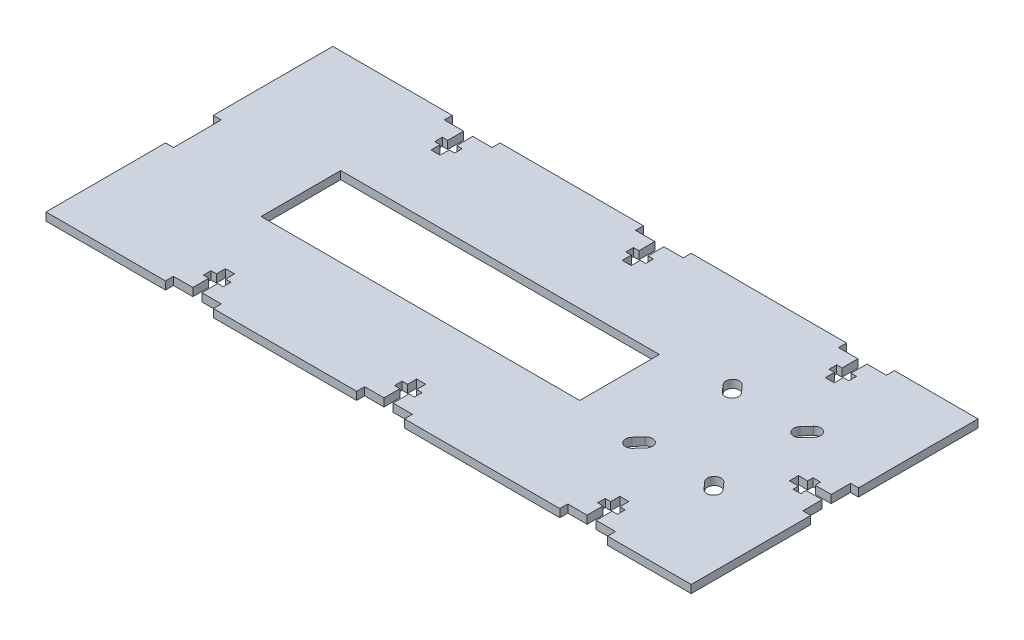
SolidWorks part; units mm, degrees
ref_plane "Front Plane" through (0, 0, 0) normal (0, 0, 1) x (1, 0, 0)
ref_plane "Top Plane" through (0, 0, 0) normal (0, 1, 0) x (1, 0, 0)
ref_plane "Right Plane" through (0, 0, 0) normal (1, 0, 0) x (0, 0, -1)
sketch "Sketch2" plane through (0, 0, 0) normal (0, 1, 0) x (1, 0, 0)
  line L0 (-102.87, -45.72) -> (-64.77, -45.72)
  line L1 (-102.87, 45.72) -> (102.87, 45.72) construction
  line L2 (-102.87, 45.72) -> (-102.87, -45.72) construction
  line L3 (-102.87, -45.72) -> (102.87, -45.72) construction
  line L4 (102.87, 45.72) -> (102.87, -45.72) construction
  line L5 (-102.87, 45.72) -> (102.87, -45.72) construction
  line L6 (-102.87, -45.72) -> (102.87, 45.72) construction
  line L7 (-64.77, -45.72) -> (-64.77, -43.18)
  line L9 (-49.53, -43.18) -> (-49.53, -45.72)
  line L10 (-49.53, -45.72) -> (-3.81, -45.72)
  line L11 (-3.81, -45.72) -> (-3.81, -43.18)
  line L12 (-3.81, -43.18) -> (11.43, -43.18) construction
  line L13 (11.43, -43.18) -> (11.43, -45.72)
  line L14 (11.43, -45.72) -> (60.96, -45.72)
  line L15 (60.96, -45.72) -> (60.96, -43.18)
  line L16 (60.96, -43.18) -> (76.2, -43.18) construction
  line L17 (76.2, -43.18) -> (76.2, -45.72)
  line L18 (76.2, -45.72) -> (102.87, -45.72)
  line L21 (-102.87, 0) -> (102.87, 0) construction
  line L22 (76.2, 43.18) -> (76.2, 45.72)
  line L23 (60.96, 43.18) -> (76.2, 43.18) construction
  line L24 (60.96, 45.72) -> (60.96, 43.18)
  line L25 (11.43, 43.18) -> (11.43, 45.72)
  line L26 (-3.81, 43.18) -> (11.43, 43.18) construction
  line L27 (-3.81, 45.72) -> (-3.81, 43.18)
  line L28 (-49.53, 43.18) -> (-49.53, 45.72)
  line L29 (-64.77, 43.18) -> (-49.53, 43.18) construction
  line L30 (-64.77, 45.72) -> (-64.77, 43.18)
  line L31 (-102.87, 45.72) -> (-64.77, 45.72)
  line L32 (-49.53, 45.72) -> (-3.81, 45.72)
  line L33 (11.43, 45.72) -> (60.96, 45.72)
  line L34 (76.2, 45.72) -> (102.87, 45.72)
  line L35 (-102.87, 45.72) -> (-102.87, 7.62)
  line L36 (-102.87, 7.62) -> (-100.33, 7.62)
  line L37 (-100.33, 7.62) -> (-100.33, -7.62)
  line L38 (-100.33, -7.62) -> (-102.87, -7.62)
  line L39 (-102.87, -7.62) -> (-102.87, -45.72)
  line L40 (0, 45.72) -> (0, -45.72) construction
  line L41 (100.33, -7.62) -> (102.87, -7.62)
  line L42 (102.87, 7.62) -> (100.33, 7.62)
  line L43 (100.33, 7.62) -> (100.33, -7.62) construction
  line L44 (102.87, 45.72) -> (102.87, 7.62)
  line L45 (102.87, -7.62) -> (102.87, -45.72)
  line L46 (-58.5978, -43.18) -> (-58.5978, -38.1)
  line L47 (-58.5978, -38.1) -> (-60.325, -38.1)
  line L48 (-60.325, -38.1) -> (-60.325, -35.668)
  line L49 (-60.325, -35.668) -> (-58.5978, -35.668)
  line L50 (-58.5978, -35.668) -> (-58.5978, -32.766)
  line L51 (-58.5978, -32.766) -> (-55.7022, -32.766)
  line L52 (-64.77, -43.18) -> (-58.5978, -43.18)
  line L53 (-49.53, -43.18) -> (-55.7022, -43.18)
  line L54 (-55.7022, -43.18) -> (-55.7022, -38.1)
  line L55 (-55.7022, -38.1) -> (-53.975, -38.1)
  line L56 (-53.975, -38.1) -> (-53.975, -35.668)
  line L57 (-64.77, -43.18) -> (-49.53, -43.18) construction
  line L58 (-57.15, -43.18) -> (-57.15, -32.766) construction
  line L59 (-53.975, -35.668) -> (-55.7022, -35.668)
  line L60 (-55.7022, -35.668) -> (-55.7022, -32.766)
  line L61 (-3.81, -43.18) -> (2.3622, -43.18)
  line L62 (2.3622, -43.18) -> (2.3622, -38.1)
  line L63 (2.3622, -38.1) -> (0.635, -38.1)
  line L64 (0.635, -38.1) -> (0.635, -35.6679)
  line L65 (0.635, -35.6679) -> (2.3622, -35.6679)
  line L66 (2.3622, -35.6679) -> (2.3622, -32.766)
  line L67 (2.3622, -32.766) -> (5.2578, -32.766)
  line L68 (3.81, -43.18) -> (3.81, -32.766) construction
  line L69 (11.43, -43.18) -> (5.2578, -43.18)
  line L70 (5.2578, -43.18) -> (5.2578, -38.1)
  line L71 (5.2578, -38.1) -> (6.985, -38.1)
  line L72 (6.985, -38.1) -> (6.985, -35.6679)
  line L73 (6.985, -35.6679) -> (5.2578, -35.6679)
  line L74 (5.2578, -35.6679) -> (5.2578, -32.766)
  line L75 (68.58, -43.18) -> (68.58, -32.766) construction
  line L76 (60.96, -43.18) -> (67.1322, -43.18)
  line L77 (67.1322, -43.18) -> (67.1322, -38.1)
  line L78 (67.1322, -38.1) -> (65.405, -38.1)
  line L79 (65.405, -38.1) -> (65.405, -35.6679)
  line L80 (65.405, -35.6679) -> (67.1322, -35.6679)
  line L81 (67.1322, -35.6679) -> (67.1322, -32.766)
  line L82 (67.1322, -32.766) -> (70.0278, -32.766)
  line L83 (70.0278, -35.6679) -> (70.0278, -32.766)
  line L84 (71.755, -35.6679) -> (70.0278, -35.6679)
  line L85 (71.755, -38.1) -> (71.755, -35.6679)
  line L86 (70.0278, -38.1) -> (71.755, -38.1)
  line L87 (76.2, -43.18) -> (70.0278, -43.18)
  line L88 (70.0278, -43.18) -> (70.0278, -38.1)
  line L89 (76.2, 43.18) -> (70.0278, 43.18)
  line L90 (70.0278, 43.18) -> (70.0278, 38.1)
  line L91 (70.0278, 38.1) -> (71.755, 38.1)
  line L92 (71.755, 38.1) -> (71.755, 35.6679)
  line L93 (71.755, 35.6679) -> (70.0278, 35.6679)
  line L94 (70.0278, 35.6679) -> (70.0278, 32.766)
  line L95 (67.1322, 32.766) -> (70.0278, 32.766)
  line L96 (67.1322, 35.6679) -> (67.1322, 32.766)
  line L97 (65.405, 35.6679) -> (67.1322, 35.6679)
  line L98 (65.405, 38.1) -> (65.405, 35.6679)
  line L99 (67.1322, 38.1) -> (65.405, 38.1)
  line L100 (67.1322, 43.18) -> (67.1322, 38.1)
  line L101 (60.96, 43.18) -> (67.1322, 43.18)
  line L102 (11.43, 43.18) -> (5.2578, 43.18)
  line L103 (5.2578, 43.18) -> (5.2578, 38.1)
  line L104 (5.2578, 38.1) -> (6.985, 38.1)
  line L105 (6.985, 38.1) -> (6.985, 35.6679)
  line L106 (6.985, 35.6679) -> (5.2578, 35.6679)
  line L107 (5.2578, 35.6679) -> (5.2578, 32.766)
  line L108 (2.3622, 32.766) -> (5.2578, 32.766)
  line L109 (0.635, 35.6679) -> (2.3622, 35.6679)
  line L110 (2.3622, 38.1) -> (0.635, 38.1)
  line L111 (0.635, 38.1) -> (0.635, 35.6679)
  line L112 (2.3622, 43.18) -> (2.3622, 38.1)
  line L113 (-3.81, 43.18) -> (2.3622, 43.18)
  line L114 (-49.53, 43.18) -> (-55.7022, 43.18)
  line L115 (-55.7022, 43.18) -> (-55.7022, 38.1)
  line L116 (-55.7022, 38.1) -> (-53.975, 38.1)
  line L117 (-53.975, 38.1) -> (-53.975, 35.6679)
  line L118 (-53.975, 35.6679) -> (-55.7022, 35.6679)
  line L119 (-55.7022, 35.6679) -> (-55.7022, 32.766)
  line L120 (-58.5978, 32.766) -> (-55.7022, 32.766)
  line L121 (-58.5978, 35.6679) -> (-58.5978, 32.766)
  line L122 (-60.325, 35.6679) -> (-58.5978, 35.6679)
  line L123 (-60.325, 38.1) -> (-60.325, 35.6679)
  line L124 (-58.5978, 38.1) -> (-60.325, 38.1)
  line L125 (-58.5978, 43.18) -> (-58.5978, 38.1)
  line L126 (-64.77, 43.18) -> (-58.5978, 43.18)
  line L127 (2.3622, 35.6679) -> (2.3622, 32.766)
  line L128 (100.33, -1.4478) -> (95.25, -1.4478)
  line L129 (95.25, -1.4478) -> (95.25, -3.175)
  line L130 (95.25, -3.175) -> (92.8179, -3.175)
  line L131 (92.8179, -3.175) -> (92.8179, -1.4478)
  line L132 (92.8179, -1.4478) -> (89.916, -1.4478)
  line L133 (89.916, -1.4478) -> (89.916, 1.4478)
  line L134 (100.33, -1.4478) -> (100.33, -7.62)
  line L135 (92.8179, 1.4478) -> (89.916, 1.4478)
  line L136 (92.8179, 3.175) -> (92.8179, 1.4478)
  line L137 (95.25, 3.175) -> (92.8179, 3.175)
  line L138 (95.25, 1.4478) -> (95.25, 3.175)
  line L139 (100.33, 1.4478) -> (95.25, 1.4478)
  line L140 (100.33, 1.4478) -> (100.33, 7.62)
  point P0 (0, 0)
  point P128 (89.916, 0)
  dimension "D1" = 205.74
  dimension "D2" = 91.44
  dimension "D3" = 38.1
  dimension "D4" = 15.24
  dimension "D5" = 2.54
  dimension "D6" = 45.72
  dimension "D7" = 49.53
  dimension "D8" = 15.24
  dimension "D9" = 2.54
  dimension "D10" = 12.954
  dimension "D11" = 5.08
  dimension "D12" = 2.432
  dimension "D13" = 6.35
  dimension "D14" = 2.8956
  dimension "D15" = 12.954
  dimension "D16" = 5.08
  dimension "D17" = 2.432
  dimension "D18" = 6.35
  dimension "D19" = 2.8956
  dimension "D20" = 12.954
  dimension "D21" = 5.08
  dimension "D22" = 2.432
  dimension "D23" = 6.35
  dimension "D24" = 2.8956
  dimension "D25" = 12.954
  dimension "D26" = 2.432
  dimension "D27" = 5.08
  dimension "D28" = 2.8956
  dimension "D29" = 6.35
extrude "Boss-Extrude1" add sketch "Sketch2" against normal blind 2.54
sketch "Sketch3" plane through (0, 0, 0) normal (0, 1, 0) x (1, 0, 0)
  line L0 (0, 0) -> (67.31, 0) construction
  line L1 (51.308, 19.05) -> (83.312, 19.05) construction
  line L2 (51.308, 19.05) -> (51.308, -19.05) construction
  line L3 (51.308, -19.05) -> (83.312, -19.05) construction
  line L4 (83.312, 19.05) -> (83.312, -19.05) construction
  line L5 (51.308, 19.05) -> (83.312, -19.05) construction
  line L6 (51.308, -19.05) -> (83.312, 19.05) construction
  line L7 (80.264, 16.002) -> (78.232, 13.7302) construction
  line L8 (81.8732, 14.5627) -> (79.8412, 12.2908)
  line L9 (78.6548, 17.4413) -> (76.6228, 15.1695)
  line L10 (67.31, 0) -> (67.31, 19.05) construction
  line L11 (54.356, 16.002) -> (56.388, 13.7302) construction
  line L12 (52.7468, 14.5627) -> (54.7788, 12.2908)
  line L13 (55.9652, 17.4413) -> (57.9972, 15.1695)
  line L14 (80.264, -16.002) -> (78.232, -13.7302) construction
  line L15 (81.8732, -14.5627) -> (79.8412, -12.2908)
  line L16 (78.6548, -17.4413) -> (76.6228, -15.1695)
  line L17 (54.356, -16.002) -> (56.388, -13.7302) construction
  line L18 (52.7468, -14.5627) -> (54.7788, -12.2908)
  line L19 (55.9652, -17.4413) -> (57.9972, -15.1695)
  arc A0 (81.8732, 14.5627) -> (78.6548, 17.4413) centre (80.264, 16.002) ccw
  arc A1 (76.6228, 15.1695) -> (79.8412, 12.2908) centre (78.232, 13.7302) ccw
  arc A2 (52.7468, 14.5627) -> (55.9652, 17.4413) centre (54.356, 16.002) cw
  arc A3 (57.9972, 15.1695) -> (54.7788, 12.2908) centre (56.388, 13.7302) cw
  arc A4 (81.8732, -14.5627) -> (78.6548, -17.4413) centre (80.264, -16.002) cw
  arc A5 (76.6228, -15.1695) -> (79.8412, -12.2908) centre (78.232, -13.7302) cw
  arc A6 (52.7468, -14.5627) -> (55.9652, -17.4413) centre (54.356, -16.002) ccw
  arc A7 (57.9972, -15.1695) -> (54.7788, -12.2908) centre (56.388, -13.7302) ccw
  point P0 (67.31, 0)
  point P8 (79.248, 14.8661)
  point P26 (55.372, 14.8661)
  point P33 (79.248, -14.8661)
  point P40 (55.372, -14.8661)
  dimension "D4" = 2.159
  dimension "D8" = 5.08
  dimension "D1" = 38.1
  dimension "D2" = 32.004
  dimension "D3" = 67.31
  dimension "D5" = 3.048
  dimension "D6" = 3.048
  dimension "D7" = 3.048
extrude "Cut-Extrude1" cut sketch "Sketch3" against normal up to next
sketch "Sketch4" plane through (0, 0, 0) normal (0, 1, 0) x (1, 0, 0)
  line L0 (102.87, 7.62) -> (102.87, 45.72) construction
  line L1 (-67.31, 12.7) -> (34.29, 12.7)
  line L2 (-67.31, 12.7) -> (-67.31, -12.7)
  line L3 (-67.31, -12.7) -> (34.29, -12.7)
  line L4 (34.29, 12.7) -> (34.29, -12.7)
  line L5 (-67.31, 12.7) -> (34.29, -12.7) construction
  line L6 (-67.31, -12.7) -> (34.29, 12.7) construction
  point P0 (-16.51, 0)
  dimension "D1" = 25.4
  dimension "D2" = 101.6
  dimension "D3" = 68.58
extrude "Cut-Extrude2" cut sketch "Sketch4" against normal up to next
